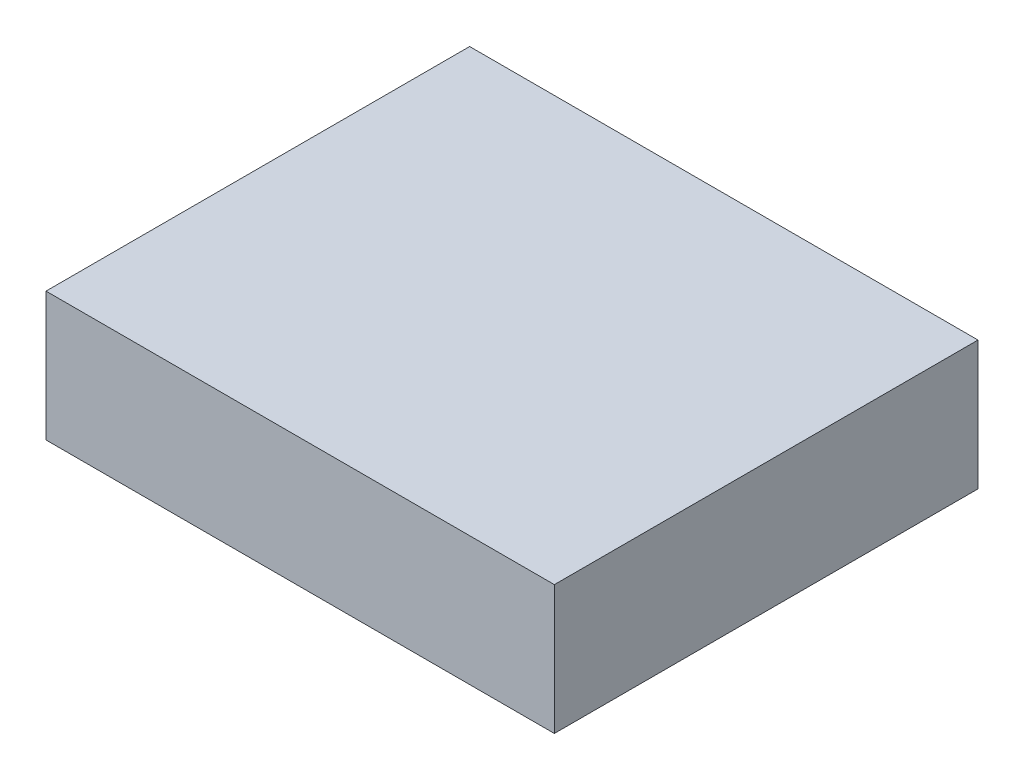
SolidWorks part; units mm, degrees
ref_plane "Front Plane" through (0, 0, 0) normal (0, 0, 1) x (1, 0, 0)
ref_plane "Top Plane" through (0, 0, 0) normal (0, 1, 0) x (1, 0, 0)
ref_plane "Right Plane" through (0, 0, 0) normal (1, 0, 0) x (0, 0, -1)
sketch "Sketch1" plane through (0, 0, 0) normal (0, 1, 0) x (1, 0, 0)
  line L1 (27.6, -23) -> (-27.6, -23)
  line L2 (27.6, -23) -> (27.6, 23)
  line L3 (27.6, 23) -> (-27.6, 23)
  line L4 (-27.6, -23) -> (-27.6, 23)
  line L5 (27.6, -23) -> (-27.6, 23) construction
  line L6 (27.6, 23) -> (-27.6, -23) construction
  point P0 (0, 0)
  dimension "D1" = 55.2
  dimension "D2" = 46
extrude "Boss-Extrude1" add sketch "Sketch1" along normal blind 14
